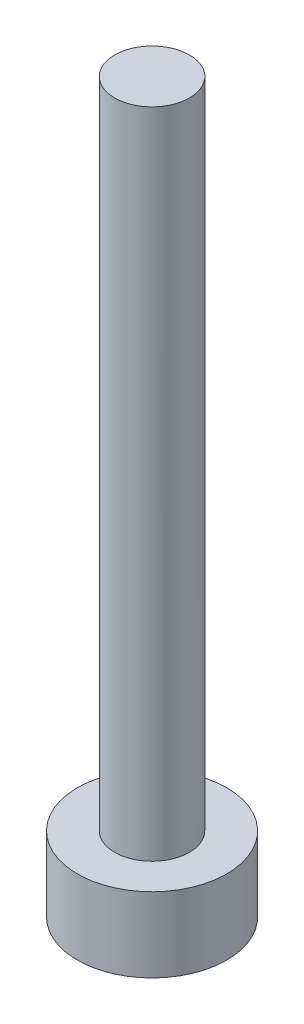
SolidWorks part; units mm, degrees
ref_plane "Front" through (0, 0, 0) normal (0, 0, 1) x (1, 0, 0)
ref_plane "Top" through (0, 0, 0) normal (0, 1, 0) x (1, 0, 0)
ref_plane "Right" through (0, 0, 0) normal (1, 0, 0) x (0, 0, -1)
sketch "草图1" plane through (0, 0, 0) normal (0, 1, 0) x (1, 0, 0)
  circle A0 centre (0, 0) radius 2
  dimension "D1" = 4
extrude "凸台-拉伸1" add sketch "草图1" along normal blind 35
sketch "草图2" plane through (0, 0, 0) normal (0, -1, 0) x (1, 0, 0)
  circle A0 centre (0, 0) radius 4
  dimension "D1" = 8
extrude "凸台-拉伸2" add sketch "草图2" along normal blind 4
